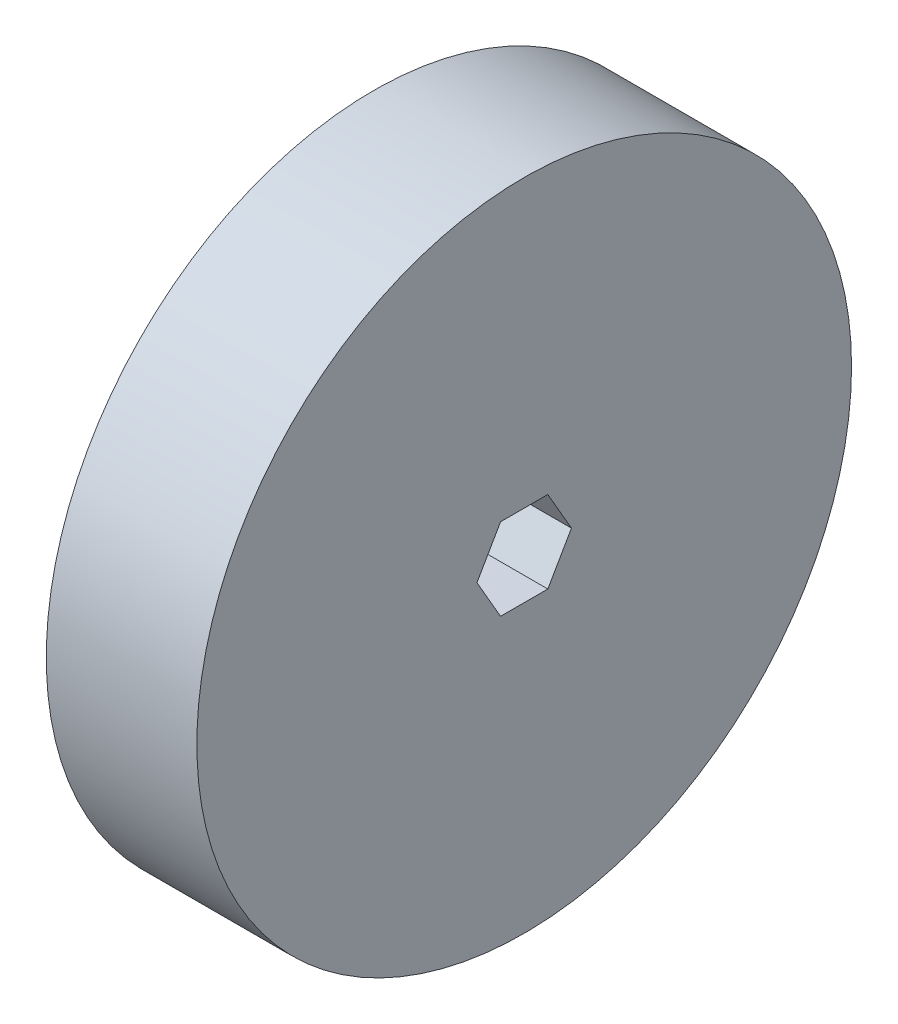
SolidWorks part; units mm, degrees
material "6061-T6 (SS)"
ref_plane "Front Plane" through (0, 0, 0) normal (0, 0, 1) x (1, 0, 0)
ref_plane "Top Plane" through (0, 0, 0) normal (0, 1, 0) x (1, 0, 0)
ref_plane "Right Plane" through (0, 0, 0) normal (1, 0, 0) x (0, 0, -1)
sketch "Sketch2" plane through (0, 0, 0) normal (1, 0, 0) x (0, 0, -1)
  line L1 (3.6662, 6.35) -> (-3.6662, 6.35)
  line L2 (-3.6662, 6.35) -> (-7.3323, 0)
  line L3 (-7.3323, 0) -> (-3.6662, -6.35)
  line L4 (-3.6662, -6.35) -> (3.6662, -6.35)
  line L5 (3.6662, -6.35) -> (7.3323, 0)
  line L6 (7.3323, 0) -> (3.6662, 6.35)
  circle A0 centre (0, 0) radius 50.8
  circle A1 centre (0, 0) radius 6.35 construction
  dimension "D1" = 101.6
  dimension "D2" = 12.7
extrude "Boss-Extrude1" add sketch "Sketch2" along normal blind 23.368
sketch "Sketch3" [suppressed] plane through (23.368, 0, 0) normal (1, 0, 0) x (0, 0, -1)
  circle A0 centre (0, 0) radius 50.8
  circle A1 centre (0, 0) radius 50.8 construction
extrude "Cut-Extrude1" [suppressed] cut sketch "Sketch3" against normal blind 27.051
sketch "Sketch5" [suppressed] plane through (23.368, 0, 0) normal (1, 0, 0) x (0, 0, -1)
  circle A0 centre (0, 0) radius 15.875
  dimension "D1" = 31.75
extrude "Cut-Extrude2" [suppressed] cut sketch "Sketch5" against normal through all
